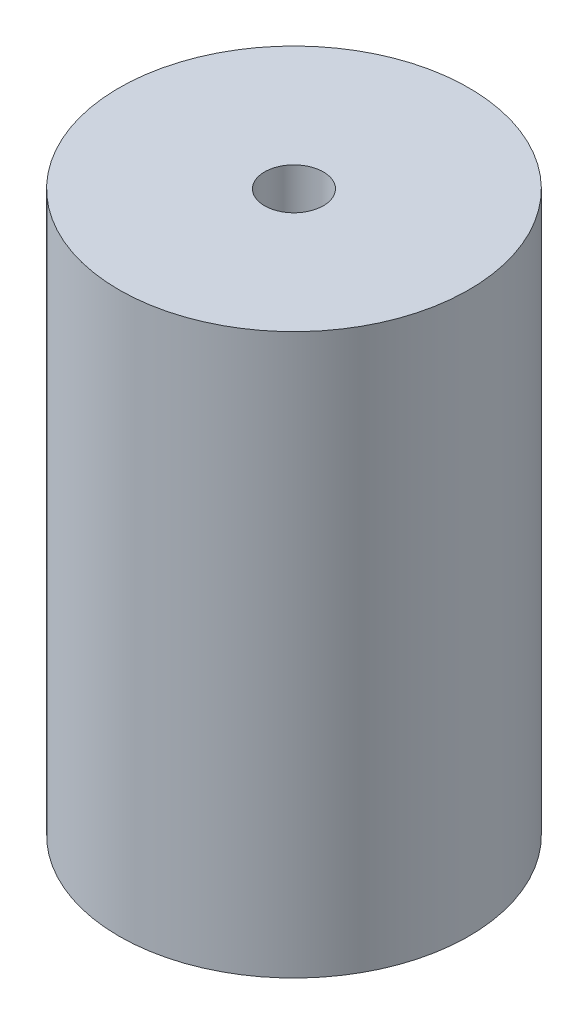
SolidWorks part; units mm, degrees
ref_plane "Alzado" through (0, 0, 0) normal (0, 0, 1) x (1, 0, 0)
ref_plane "Planta" through (0, 0, 0) normal (0, 1, 0) x (1, 0, 0)
ref_plane "Vista lateral" through (0, 0, 0) normal (1, 0, 0) x (0, 0, -1)
sketch "Croquis1" plane through (0, 0, 0) normal (0, 1, 0) x (1, 0, 0)
  circle A0 centre (0, 0) radius 12.5
  dimension "D1" = 25
extrude "Saliente-Extruir1" add sketch "Croquis1" along normal blind 40
sketch "Sketch1" plane through (0, 40, 0) normal (0, 1, 0) x (1, 0, 0)
  circle A0 centre (0, 0) radius 2.1
  dimension "D1" = 4.2
extrude "Cut-Extrude1" cut sketch "Sketch1" against normal blind 21
